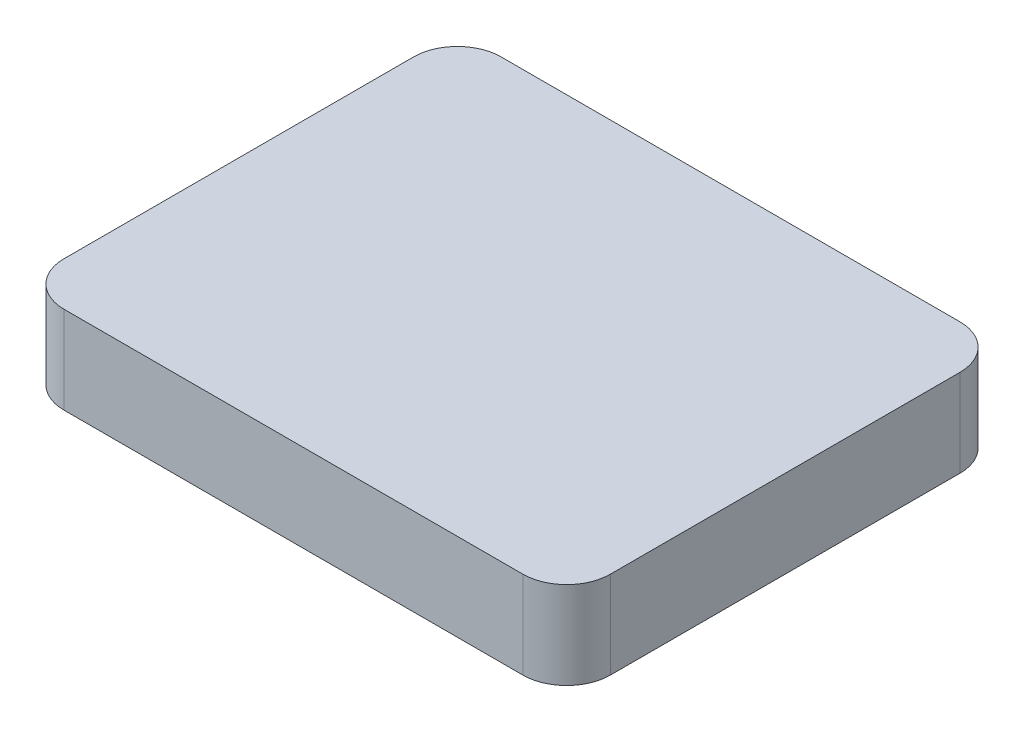
SolidWorks part; units mm, degrees
ref_plane "Front Plane" through (0, 0, 0) normal (0, 0, 1) x (1, 0, 0)
ref_plane "Top Plane" through (0, 0, 0) normal (0, 1, 0) x (1, 0, 0)
ref_plane "Right Plane" through (0, 0, 0) normal (1, 0, 0) x (0, 0, -1)
sketch "Sketch1" plane through (0, 0, 0) normal (0, 1, 0) x (1, 0, 0)
  line L1 (-125, -100) -> (125, -100)
  line L2 (-125, -100) -> (-125, 100)
  line L3 (-125, 100) -> (125, 100)
  line L4 (125, -100) -> (125, 100)
  line L5 (-125, -100) -> (125, 100) construction
  line L6 (-125, 100) -> (125, -100) construction
  point P0 (0, 0)
  dimension "D1" = 250
  dimension "D2" = 200
extrude "Boss-Extrude1" add sketch "Sketch1" along normal blind 40
fillet "Fillet1" radius 20 4 edges at (-125, 20, 100) (-125, 20, -100) (125, 20, -100) (125, 20, 100)
